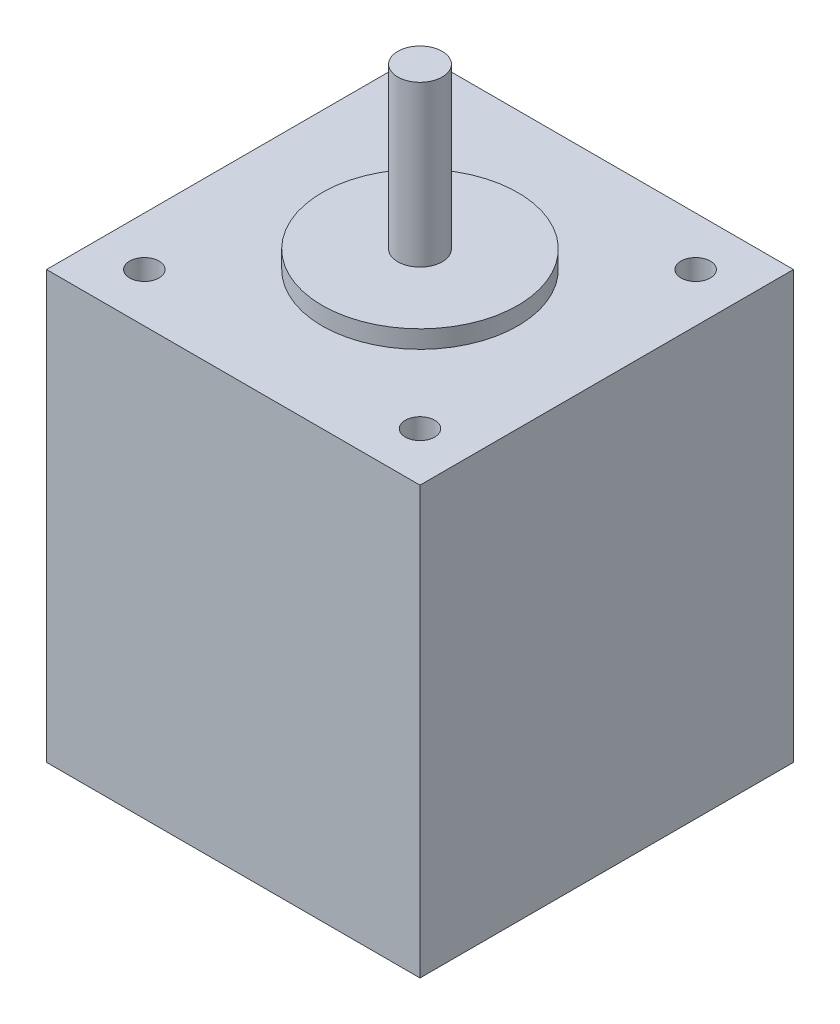
SolidWorks part; units mm, degrees
ref_plane "Front Plane" through (0, 0, 0) normal (0, 0, 1) x (1, 0, 0)
ref_plane "Top Plane" through (0, 0, 0) normal (0, 1, 0) x (1, 0, 0)
ref_plane "Right Plane" through (0, 0, 0) normal (1, 0, 0) x (0, 0, -1)
sketch "Sketch1" plane through (0, 0, 0) normal (0, 1, 0) x (1, 0, 0)
  line L1 (21, -21) -> (-21, -21)
  line L2 (21, -21) -> (21, 21)
  line L3 (21, 21) -> (-21, 21)
  line L4 (-21, -21) -> (-21, 21)
  line L5 (21, -21) -> (-21, 21) construction
  line L6 (21, 21) -> (-21, -21) construction
  point P0 (0, 0)
  dimension "D1" = 42
  dimension "D2" = 42
extrude "Boss-Extrude1" add sketch "Sketch1" along normal blind 48
sketch "Sketch2" plane through (0, 48, 0) normal (0, 1, 0) x (1, 0, 0)
  circle A0 centre (0, 0) radius 2.5
  dimension "D1" = 5
extrude "Boss-Extrude2" add sketch "Sketch2" along normal blind 20
hole_wizard "Tap Drill for M4x0.7 Tap1" positions "Sketch3" profile "Sketch4" hole size "M4x0.7" standard "ANSI Metric"
sketch "Sketch3" plane through (0, 48, 0) normal (0, 1, 0) x (1, 0, 0)
  line L1 (15.5, -15.5) -> (-15.5, -15.5) construction
  line L2 (15.5, -15.5) -> (15.5, 15.5) construction
  line L3 (15.5, 15.5) -> (-15.5, 15.5) construction
  line L4 (-15.5, -15.5) -> (-15.5, 15.5) construction
  line L5 (15.5, -15.5) -> (-15.5, 15.5) construction
  line L6 (15.5, 15.5) -> (-15.5, -15.5) construction
  point P0 (-15.5, 15.5)
  point P2 (-15.5, -15.5)
  point P4 (15.5, -15.5)
  point P6 (15.5, 15.5)
  point P9 (0, 0)
  dimension "D1" = 31
  dimension "D2" = 31
sketch "Sketch4" plane through (-15.5, 48, -15.5) normal (1, 0, 0) x (0, 0, 1)
  line L0 (0, 0) -> (0, 48)
  line L1 (0, 48) -> (1.65, 48)
  line L2 (1.65, 48) -> (1.65, 0)
  line L5 (1.65, 0) -> (0, 0)
  line L11 (0, -6.35) -> (0, 107.95) construction
  dimension "Thru Hole Dia." = 3.3
  dimension "Thru Hole Depth" = 48
sketch "Sketch5" plane through (0, 0, 0) normal (0, -1, 0) x (1, 0, 0)
  line L0 (0, -1.65) -> (0, 1.65) construction
  line L1 (-1.65, 0) -> (1.65, 0) construction
  circle A0 centre (0, 0) radius 1.65 construction
  point P7 (0, 0)
sketch "Sketch6" plane through (0, 48, 0) normal (0, 1, 0) x (1, 0, 0)
  circle A0 centre (0, 0) radius 11
  dimension "D1" = 22
extrude "Boss-Extrude3" add sketch "Sketch6" along normal blind 2
